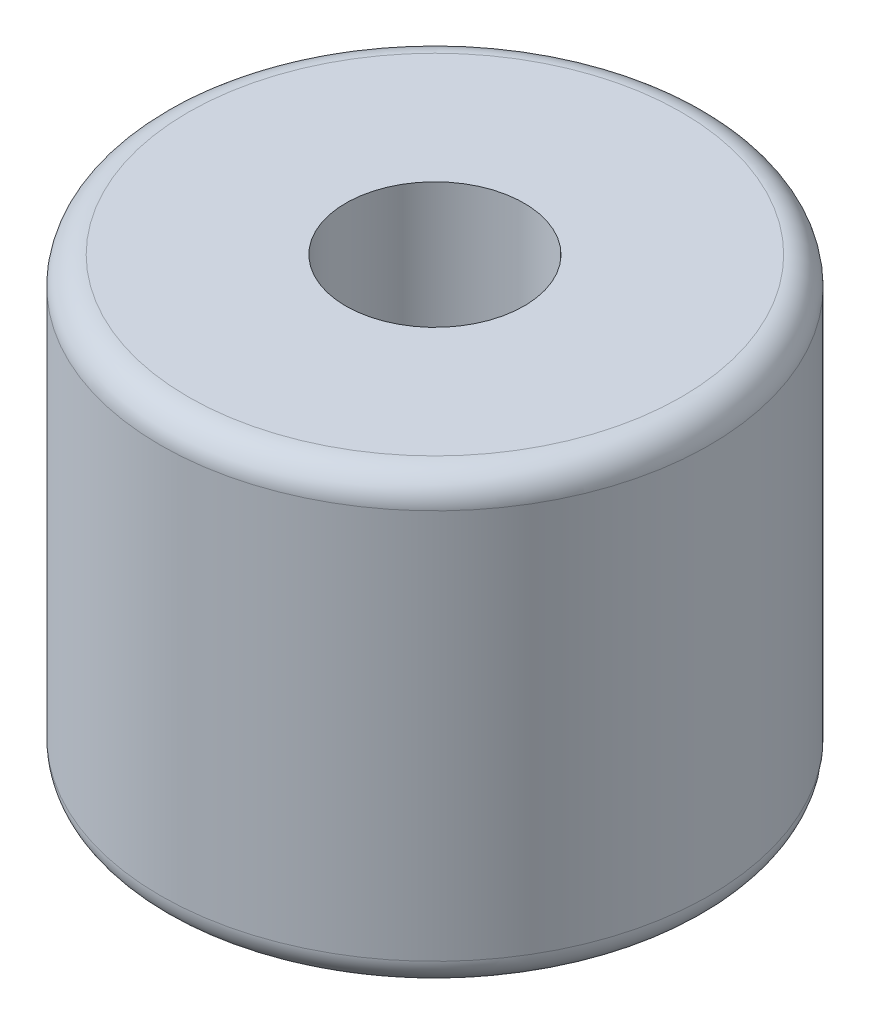
SolidWorks part; units mm, degrees
ref_plane "前视基准面" through (0, 0, 0) normal (0, 0, 1) x (1, 0, 0)
ref_plane "上视基准面" through (0, 0, 0) normal (0, 1, 0) x (1, 0, 0)
ref_plane "右视基准面" through (0, 0, 0) normal (1, 0, 0) x (0, 0, -1)
sketch "草图1" plane through (0, 0, 0) normal (0, 1, 0) x (1, 0, 0)
  circle A0 centre (0, 0) radius 4.925
  circle A1 centre (0, 0) radius 1.6
  dimension "D1" = 9.85
  dimension "D2" = 3.2
extrude "凸台-拉伸1" add sketch "草图1" along normal blind 8
fillet "圆角1" radius 0.5 3 edges at (0, 8, 4.925) (0, 0, 1.6) (0, 0, 4.925)
